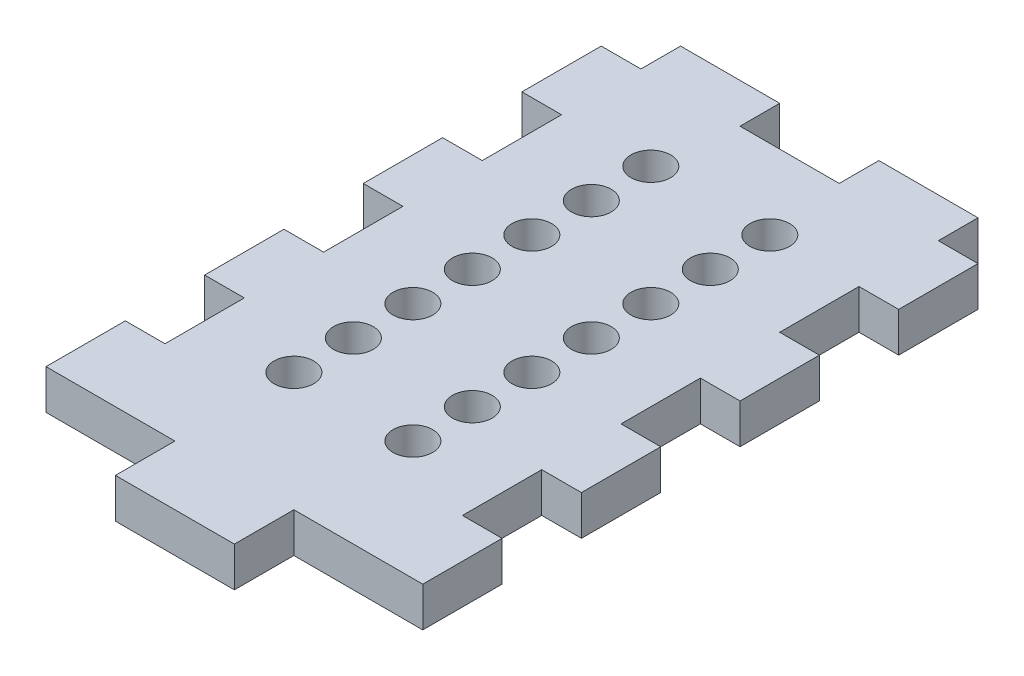
SolidWorks part; units mm, degrees
ref_plane "Front Plane" through (0, 0, 0) normal (0, 0, 1) x (1, 0, 0)
ref_plane "Top Plane" through (0, 0, 0) normal (0, 1, 0) x (1, 0, 0)
ref_plane "Right Plane" through (0, 0, 0) normal (1, 0, 0) x (0, 0, -1)
other "Configuration Table"
sketch "Sketch1" plane through (0, 0, 0) normal (0, 1, 0) x (1, 0, 0)
  line L5 (-15, 30) -> (15, -30) construction
  line L6 (-15, -30) -> (15, 30) construction
  line L11 (0, 30) -> (0, -30) construction
  line L15 (-5, 26) -> (5, 26)
  line L17 (-15, 30) -> (-15, 26)
  line L20 (-15, 30) -> (-5, 30)
  line L21 (-15, 30) -> (-15, 26)
  line L23 (-5, 30) -> (-5, 26)
  line L24 (15, 30) -> (5, 30)
  line L27 (5, 30) -> (5, 26)
  line L28 (-15, -30) -> (-6, -30)
  line L30 (-6, -30) -> (-6, -36)
  line L31 (-6, -36) -> (6, -36)
  line L32 (6, -30) -> (6, -36)
  line L33 (6, -30) -> (15, -30)
  line L34 (-15, -22) -> (-15, -14)
  line L35 (-15, 26) -> (-19, 26)
  line L37 (-15, -30) -> (-19, -30)
  line L39 (-19, 26) -> (-15, 26)
  line L40 (-19, 26) -> (-19, 18)
  line L41 (-19, 18) -> (-15, 18)
  line L43 (-19, 10) -> (-15, 10)
  line L44 (-19, 10) -> (-19, 2)
  line L45 (-19, 2) -> (-15, 2)
  line L47 (-19, -6) -> (-15, -6)
  line L48 (-19, -6) -> (-19, -14)
  line L49 (-19, -14) -> (-15, -14)
  line L51 (-15, -30) -> (-19, -30)
  line L53 (-15, -22) -> (-19, -22)
  line L54 (-19, -30) -> (-19, -22)
  line L55 (-15, -6) -> (-15, 2)
  line L56 (-15, 10) -> (-15, 18)
  line L57 (15, -30) -> (19, -30)
  line L58 (19, -30) -> (19, -22)
  line L59 (15, -22) -> (19, -22)
  line L60 (15, -22) -> (15, -14)
  line L61 (19, -14) -> (15, -14)
  line L62 (19, -6) -> (19, -14)
  line L63 (19, -6) -> (15, -6)
  line L64 (15, -6) -> (15, 2)
  line L65 (19, 2) -> (15, 2)
  line L66 (19, 10) -> (19, 2)
  line L67 (19, 10) -> (15, 10)
  line L68 (15, 10) -> (15, 18)
  line L69 (19, 18) -> (15, 18)
  line L70 (19, 26) -> (19, 18)
  line L71 (15, 26) -> (19, 26)
  line L72 (15, 30) -> (15, 26)
  arc A0 (-8, 18) -> (-4, 18) centre (-6, 18) cw
  arc A1 (-8, -18) -> (-4, -18) centre (-6, -18) ccw
  circle A4 centre (-6, 18) radius 2
  circle A5 centre (-6, 12) radius 2
  circle A6 centre (-6, 6) radius 2
  circle A7 centre (-6, 0) radius 2
  circle A8 centre (-6, -6) radius 2
  circle A9 centre (-6, -12) radius 2
  circle A10 centre (-6, -18) radius 2
  circle A11 centre (6, -18) radius 2
  circle A12 centre (6, -12) radius 2
  circle A13 centre (6, -6) radius 2
  circle A14 centre (6, 0) radius 2
  circle A15 centre (6, 6) radius 2
  circle A16 centre (6, 12) radius 2
  circle A17 centre (6, 18) radius 2
  arc A18 (8, -18) -> (4, -18) centre (6, -18) cw
  arc A19 (8, 18) -> (4, 18) centre (6, 18) ccw
  point P0 (0, 0)
  point P6 (0, 0)
  point P47 (-17, 2)
  dimension "D5" = 10
  dimension "D20" = 7
  dimension "D1" = 60
  dimension "D2" = 30
  dimension "D3" = 6
  dimension "D4" = 36
  dimension "D6" = 10
  dimension "D7" = 4
  dimension "D8" = 6
  dimension "D9" = 4
  dimension "D10" = 8
  dimension "D11" = 10
  dimension "D12" = 8
  dimension "D13" = 8
  dimension "D14" = 8
  dimension "D15" = 8
  dimension "D16" = 8
  dimension "D17" = 8
  dimension "D18" = 4
  dimension "D19" = 12
extrude "Boss-Extrude1" add sketch "Sketch1" along normal blind 4
